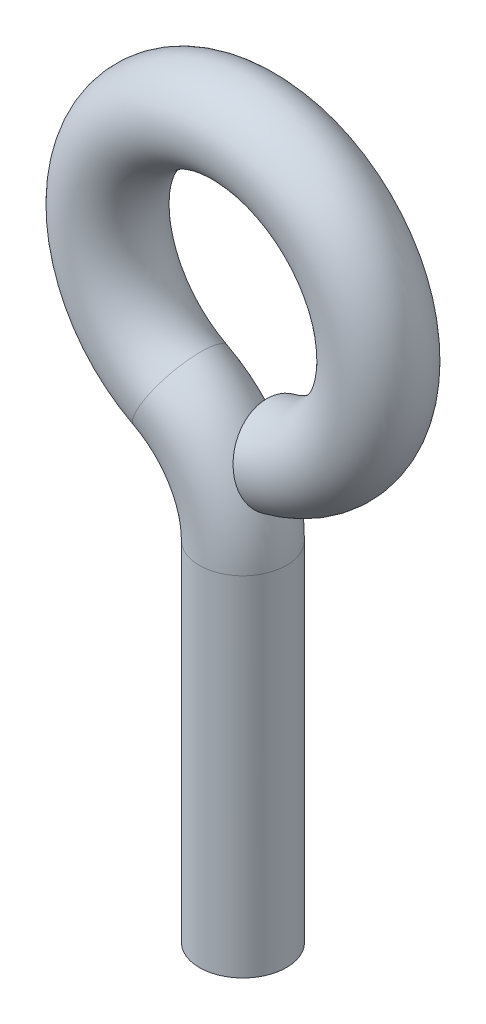
SolidWorks part; units mm, degrees
ref_plane "Front Plane" through (0, 0, 0) normal (0, 0, 1) x (1, 0, 0)
ref_plane "Top Plane" through (0, 0, 0) normal (0, 1, 0) x (1, 0, 0)
ref_plane "Right Plane" through (0, 0, 0) normal (1, 0, 0) x (0, 0, -1)
sketch "Sketch1" plane through (0, 0, 0) normal (0, 0, 1) x (1, 0, 0)
  line L0 (0, 0) -> (0, 18)
  line L1 (1.8117, 22.7803) -> (0, 29.5418) construction
  arc A0 (0, 18) -> (-3.2352, 23.3342) centre (-6.0152, 18) ccw
  arc A1 (-3.2352, 23.3342) -> (1.8117, 22.7803) centre (0, 29.5418) cw
  point P8 (0.7637, 36.5)
  dimension "D2" = 7
  dimension "D1" = 36.5
  dimension "D3" = 18
  dimension "D4" = 15
sketch "Sketch2" plane through (0, 0, 0) normal (0, 1, 0) x (1, 0, 0)
  circle A0 centre (0, 0) radius 2.25
  dimension "D1" = 4.5
sweep "Sweep1" add profiles "Sketch2" path "Sketch1"
